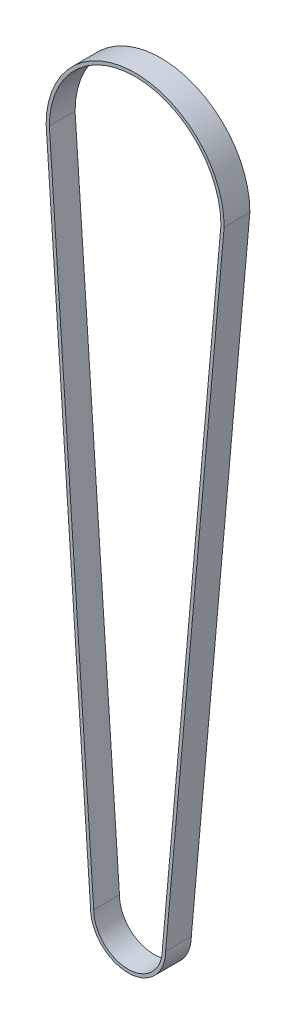
SolidWorks part; units mm, degrees
ref_plane "Front Plane" through (0, 0, 0) normal (0, 0, 1) x (1, 0, 0)
ref_plane "Top Plane" through (0, 0, 0) normal (0, 1, 0) x (1, 0, 0)
ref_plane "Right Plane" through (0, 0, 0) normal (1, 0, 0) x (0, 0, -1)
sketch "Sketch2" plane through (0, 0, 0) normal (0, 0, 1) x (1, 0, 0)
  line L0 (-19.4905, 69.9017) -> (-9.1414, -83.1394)
  line L1 (20.5095, 69.9017) -> (6.8586, -83.1394)
  line L2 (-20.2405, 69.8761) -> (-9.8914, -83.1653)
  line L3 (21.2595, 69.868) -> (7.6085, -83.1736)
  arc A0 (-19.4905, 69.9017) -> (20.5095, 69.9017) centre (0.5095, 69.9017) cw
  arc A1 (-9.1414, -83.1394) -> (6.8586, -83.1394) centre (-1.1414, -83.1394) ccw
  arc A2 (-9.8914, -83.1653) -> (7.6085, -83.1736) centre (-1.1414, -83.1394) ccw
  arc A3 (-20.2405, 69.8761) -> (21.2595, 69.868) centre (0.5095, 69.9017) cw
  dimension "D1" = 0.75
extrude "Boss-Extrude1" add sketch "Sketch2" along normal blind 6
